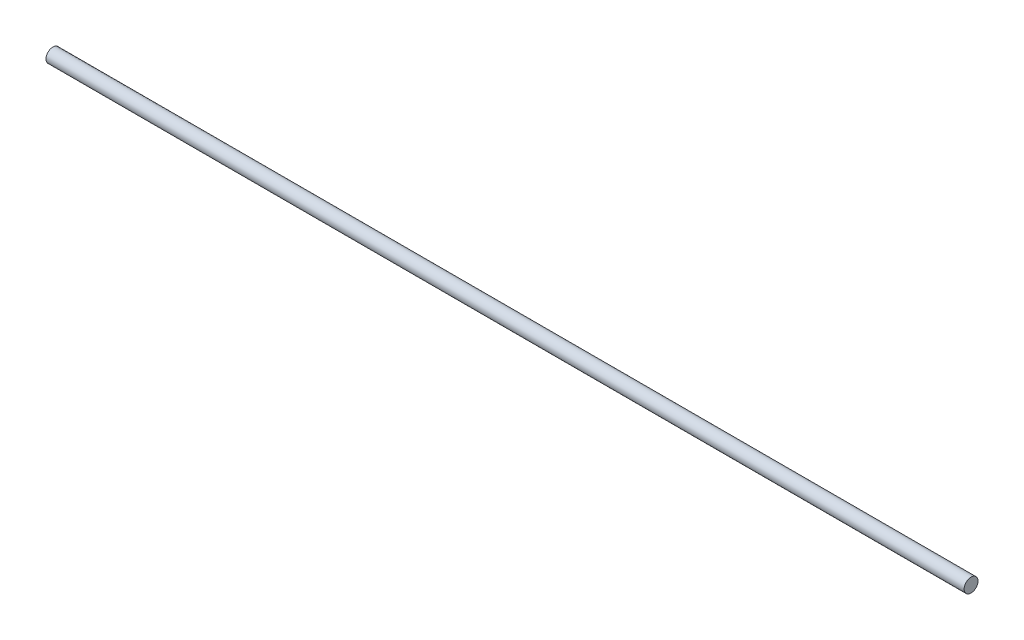
SolidWorks part; units mm, degrees
ref_plane "Front Plane" through (0, 0, 0) normal (0, 0, 1) x (1, 0, 0)
ref_plane "Top Plane" through (0, 0, 0) normal (0, 1, 0) x (1, 0, 0)
ref_plane "Right Plane" through (0, 0, 0) normal (1, 0, 0) x (0, 0, -1)
sketch "Sketch1" plane through (0, 0, 0) normal (1, 0, 0) x (0, 0, -1)
  circle A0 centre (0, 0) radius 4
  dimension "D1" = 8
extrude "Boss-Extrude1" add sketch "Sketch1" along normal blind 530
